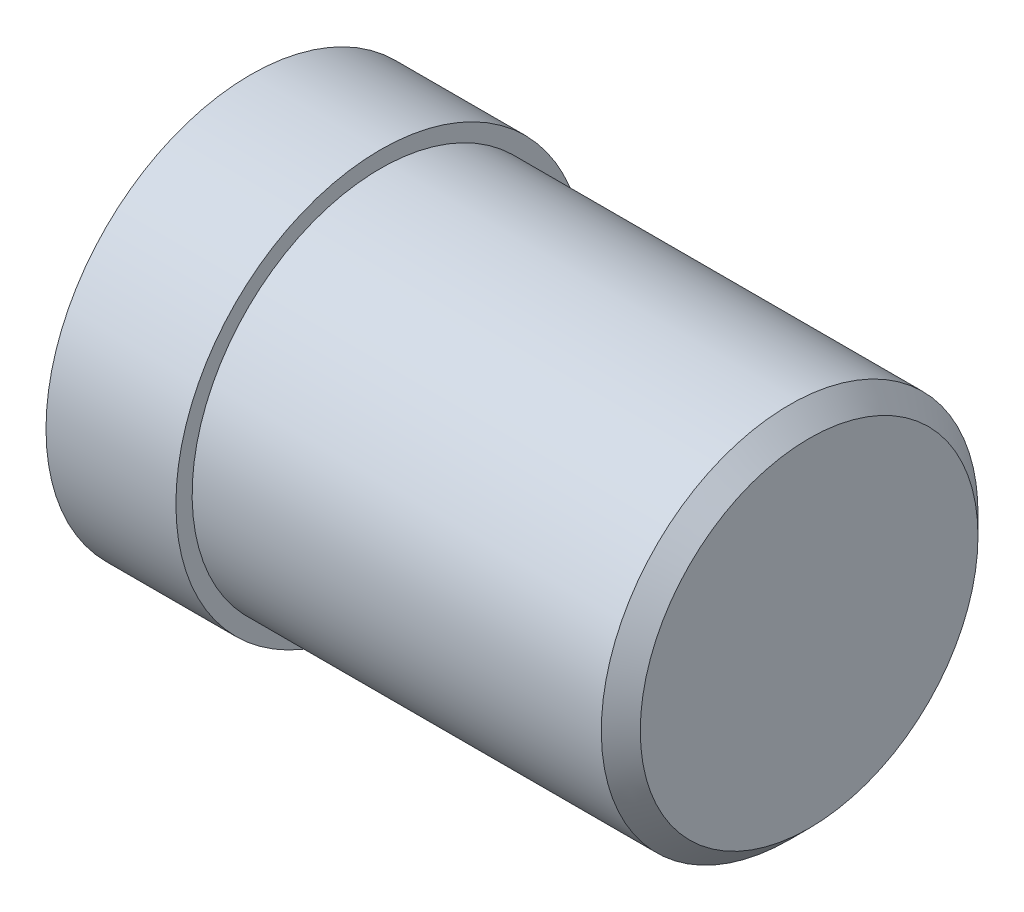
SolidWorks part; units mm, degrees
ref_plane "Plano frontal" through (0, 0, 0) normal (0, 0, 1) x (1, 0, 0)
ref_plane "Plano superior" through (0, 0, 0) normal (0, 1, 0) x (1, 0, 0)
ref_plane "Plano direito" through (0, 0, 0) normal (1, 0, 0) x (0, 0, -1)
sketch "Esboço1" plane through (0, 0, 0) normal (0, 0, 1) x (1, 0, 0)
  line L0 (0, 0) -> (8.6, 0) construction
  line L1 (8.3, 2.9) -> (8.6, 2.6)
  line L2 (8.6, 2.55) -> (8.6, 0)
  line L3 (0, 3.15) -> (2, 3.15)
  line L4 (2, 3.15) -> (2, 2.9)
  line L5 (2, 2.9) -> (8.3, 2.9)
  line L6 (8.6, 2.6) -> (8.6, 2.55)
  line L7 (0, 3.15) -> (0, 2.55)
  line L8 (0, 2.55) -> (8.45, 2.55)
  line L9 (8.6, 0) -> (8.45, 0)
  line L10 (8.45, 0) -> (8.45, 2.55)
  point P9 (8.6, 2.9)
  point P11 (0, 2.85)
  dimension "D1" = 2
  dimension "D2" = 0.25
  dimension "D3" = 8.6
  dimension "D4" = 0.6
  dimension "D6" = 8.45
revolve "Revolução1" add sketch "Esboço1" angle 360 about L0
sketch "Esboço2" plane through (0, 0, 0) normal (1, 0, 0) x (0, 0, -1)
  circle A0 centre (0, 0) radius 2.8489
  dimension "D1" = 5.6977
extrude "Corte-extrusão1" cut sketch "Esboço2" along normal blind 0.2
